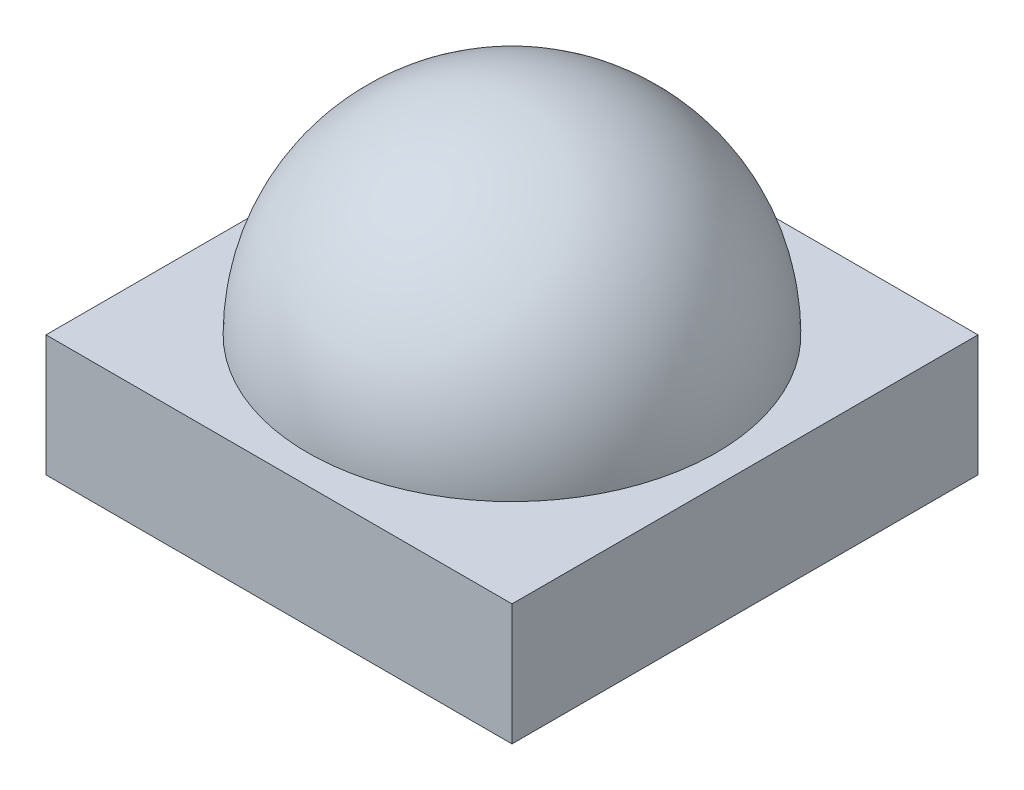
SolidWorks part; units mm, degrees
ref_plane "Front Plane" through (0, 0, 0) normal (0, 0, 1) x (1, 0, 0)
ref_plane "Top Plane" through (0, 0, 0) normal (0, 1, 0) x (1, 0, 0)
ref_plane "Right Plane" through (0, 0, 0) normal (1, 0, 0) x (0, 0, -1)
sketch "Sketch1" plane through (0, 0, 0) normal (0, 1, 0) x (1, 0, 0)
  line L1 (-1.825, -1.825) -> (1.825, -1.825)
  line L2 (-1.825, -1.825) -> (-1.825, 1.825)
  line L3 (-1.825, 1.825) -> (1.825, 1.825)
  line L4 (1.825, -1.825) -> (1.825, 1.825)
  line L5 (-1.825, -1.825) -> (1.825, 1.825) construction
  line L6 (-1.825, 1.825) -> (1.825, -1.825) construction
  point P0 (0, 0)
  dimension "D1" = 3.65
extrude "Boss-Extrude1" add sketch "Sketch1" along normal blind 0.95
sketch "Sketch2" plane through (0, 0.95, 0) normal (0, 1, 0) x (1, 0, 0)
  line L0 (0, 1.6) -> (0, -1.6)
  arc A0 (0, 1.6) -> (0, -1.6) centre (0, 0) cw
  dimension "D1" = 1.6
revolve "Revolve1" add sketch "Sketch2" angle 180 about L0
